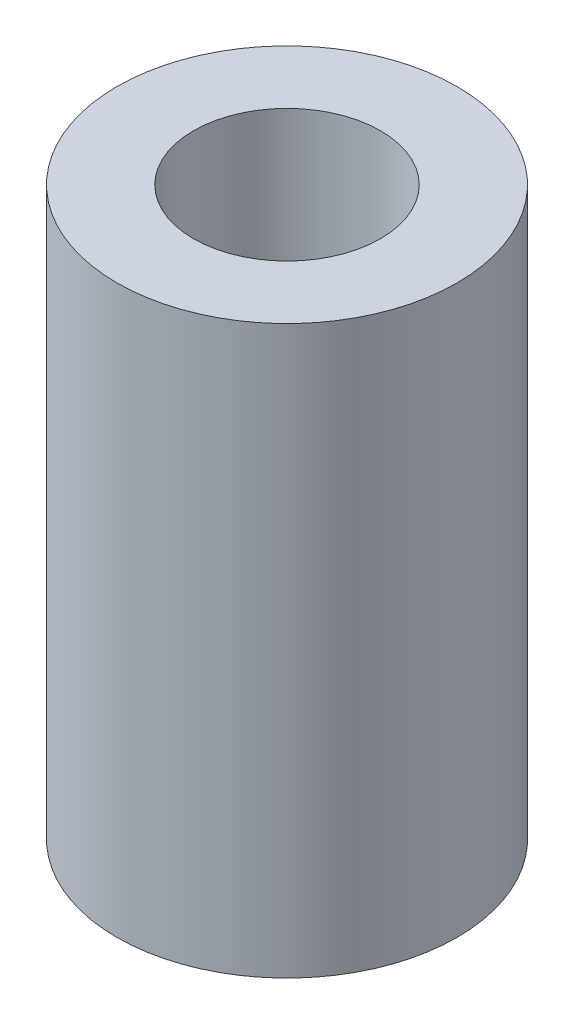
SolidWorks part; units mm, degrees
material "Brass"
ref_plane "Front Plane" through (0, 0, 0) normal (0, 0, 1) x (1, 0, 0)
ref_plane "Top Plane" through (0, 0, 0) normal (0, 1, 0) x (1, 0, 0)
ref_plane "Right Plane" through (0, 0, 0) normal (1, 0, 0) x (0, 0, -1)
sketch "Sketch1" plane through (0, 0, 0) normal (0, 1, 0) x (1, 0, 0)
  circle A0 centre (0, 0) radius 3
  dimension "D1" = 6
extrude "Boss-Extrude1" add sketch "Sketch1" along normal blind 10
hole_wizard "M4x0.7 Tapped Hole1" positions "Sketch2" profile "Sketch3" tap size "M4x0.7" standard "ANSI Metric" end condition through all
sketch "Sketch2" plane through (0, 10, 0) normal (0, 1, 0) x (1, 0, 0)
  point P0 (0, 0)
sketch "Sketch3" plane through (0, 10, 0) normal (1, 0, 0) x (0, 0, 1)
  line L0 (0, 0) -> (0, 10)
  line L1 (0, 10) -> (1.65, 10)
  line L2 (1.65, 10) -> (1.65, 0)
  line L5 (1.65, 0) -> (0, 0)
  line L11 (0, -6.35) -> (0, 107.95) construction
  dimension "Thru Tap Drill Dia." = 3.3
  dimension "Thru Tap Drill Depth" = 10
cosmetic thread "Hole Thread1"
